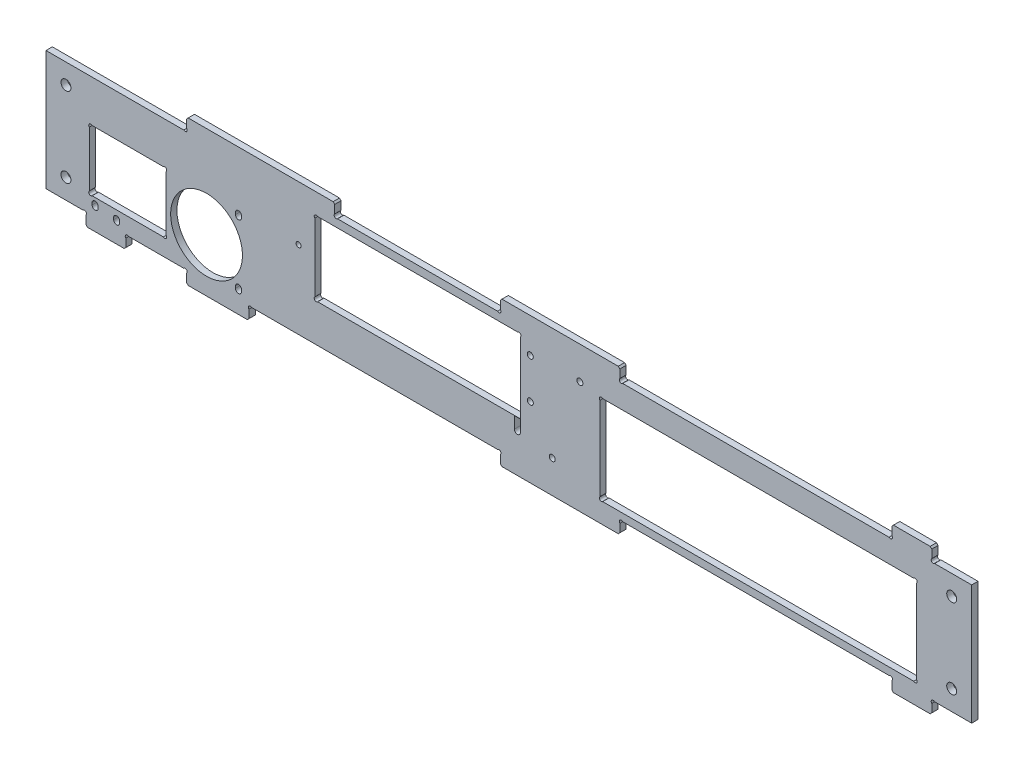
SolidWorks part; units mm, degrees
ref_plane "Front Plane" through (0, 0, 0) normal (0, 0, 1) x (1, 0, 0)
ref_plane "Top Plane" through (0, 0, 0) normal (0, 1, 0) x (1, 0, 0)
ref_plane "Right Plane" through (0, 0, 0) normal (1, 0, 0) x (0, 0, -1)
sketch "Sketch1" plane through (0, 0, 0) normal (0, 0, -1) x (-1, 0, 0)
  line L1 (-443.68, 0) -> (20.2, 0)
  line L2 (-443.68, 0) -> (-443.68, 60)
  line L3 (-443.68, 60) -> (20.2, 60)
  line L4 (20.2, 0) -> (20.2, 60)
extrude "Boss-Extrude1" add sketch "Sketch1" along normal up to vertex (3.175 mm away)
sketch "Sketch7" plane through (0, 0, -3.175) normal (0, 0, -1) x (-1, 0, 0)
  line L0 (-433.68, 50) -> (-433.68, 10) construction
  line L1 (10.2, 50) -> (10.2, 10) construction
  circle A0 centre (-433.68, 30) radius 2.5 construction
  circle A1 centre (10.2, 30) radius 2.5 construction
  circle A2 centre (-433.68, 50) radius 2.5
  circle A3 centre (-433.68, 10) radius 2.5
  circle A4 centre (10.2, 10) radius 2.5
  circle A5 centre (10.2, 50) radius 2.5
  point P10 (-433.68, 30)
  point P11 (10.2, 30)
  dimension "D2" = 5
  dimension "D1" = 20
extrude "Cut-Extrude5" cut sketch "Sketch7" against normal through all
sketch "Sketch2" plane through (0, 0, -3.175) normal (0, 0, -1) x (-1, 0, 0)
  line L0 (-216.5, 19) -> (-216.5, 58) construction
  line L1 (-217.5, 56) -> (-114.5, 56)
  line L2 (-217.5, 56) -> (-217.5, 19)
  line L3 (-217.5, 19) -> (-114.5, 19)
  line L4 (-114.5, 56) -> (-114.5, 19)
  line L5 (-107.5, 58) -> (-216.5, 58) construction
  line L6 (-216.5, 19) -> (-108.5, 19) construction
  line L7 (-108.5, 39) -> (-103.5, 44) construction
  line L8 (-103.5, 34) -> (-108.5, 39) construction
  line L9 (-222.5, 49) -> (-222.5, 29) construction
  line L10 (-217.5, 13) -> (-214.5, 13) construction
  line L11 (-217.5, 13) -> (-217.5, 18.9)
  line L12 (-217.5, 18.9) -> (-214.5, 18.9)
  line L13 (-214.5, 13) -> (-214.5, 18.9)
  line L14 (-216, 18.9) -> (-216, 13) construction
  line L15 (-217.5, 15.95) -> (-214.5, 15.95) construction
  circle A0 centre (-106.3787, 39) radius 1.5 construction
  circle A1 centre (-106.3787, 39) radius 1.25
  arc A2 (-217.5, 13) -> (-214.5, 13) centre (-216, 13) ccw
  circle A3 centre (-222.5, 49) radius 1.5
  circle A4 centre (-222.5, 29) radius 1.5
  point P18 (-216, 15.95)
  point P22 (-216, 11.5)
  point P27 (-222.5, 39)
  dimension "D4" = 3
  dimension "D5" = 2.5
  dimension "D9" = 3
  dimension "D1" = 1
  dimension "D2" = 6
  dimension "D3" = 2
  dimension "D6" = 0.1
  dimension "D7" = 3
  dimension "D8" = 6
  dimension "D10" = 5
  dimension "D11" = 20
extrude "Cut-Extrude1" cut sketch "Sketch2" against normal through all
sketch "Sketch3" plane through (0, 0, -3.175) normal (0, 0, -1) x (-1, 0, 0)
  line L1 (-257.37, 3.7) -> (-416.12, 3.7)
  line L2 (-257.37, 3.7) -> (-257.37, 48.4)
  line L3 (-257.37, 48.4) -> (-416.12, 48.4)
  line L4 (-416.12, 3.7) -> (-416.12, 48.4)
  line L5 (-336.745, 48.4) -> (-336.745, 3.7) construction
  line L6 (-257.37, 26.05) -> (-416.12, 26.05) construction
  point P0 (-336.745, 26.05)
extrude "Cut-Extrude2" cut sketch "Sketch3" against normal through all
sketch "Sketch4" plane through (0, 0, -3.175) normal (0, 0, -1) x (-1, 0, 0)
  line L1 (-76.25, 4.25) -> (-76.25, 5.25) construction
  line L2 (-77.75, 4.25) -> (-77.75, 5.25)
  line L3 (-74.75, 4.25) -> (-74.75, 5.25)
  line L4 (-76.25, 36.25) -> (-76.25, 37.25) construction
  line L5 (-77.75, 36.25) -> (-77.75, 37.25)
  line L6 (-74.75, 36.25) -> (-74.75, 37.25)
  line L7 (-15.2, 3.5) -> (-15.2, 4.5) construction
  line L8 (-16.7, 3.5) -> (-16.7, 4.5)
  line L9 (-13.7, 3.5) -> (-13.7, 4.5)
  line L10 (-4.4, 4.5) -> (-4.4, 5.5) construction
  line L11 (-5.9, 4.5) -> (-5.9, 5.5)
  line L12 (-2.9, 4.5) -> (-2.9, 5.5)
  line L13 (-40, 0) -> (-40, 40.5) construction
  line L14 (-1.5, 39) -> (-40, 39)
  line L15 (-1.5, 39) -> (-1.5, 8.5)
  line L16 (-1.5, 8.5) -> (-40, 8.5)
  line L17 (-40, 39) -> (-40, 8.5)
  line L18 (-81.5, 40.5) -> (0, 40.5) construction
  line L19 (0, 40.5) -> (0, 0) construction
  arc A0 (-77.75, 4.25) -> (-74.75, 4.25) centre (-76.25, 4.25) ccw
  arc A1 (-74.75, 5.25) -> (-77.75, 5.25) centre (-76.25, 5.25) ccw
  arc A2 (-77.75, 36.25) -> (-74.75, 36.25) centre (-76.25, 36.25) ccw
  arc A3 (-74.75, 37.25) -> (-77.75, 37.25) centre (-76.25, 37.25) ccw
  arc A4 (-16.7, 3.5) -> (-13.7, 3.5) centre (-15.2, 3.5) ccw
  arc A5 (-13.7, 4.5) -> (-16.7, 4.5) centre (-15.2, 4.5) ccw
  arc A6 (-5.9, 4.5) -> (-2.9, 4.5) centre (-4.4, 4.5) ccw
  arc A7 (-2.9, 5.5) -> (-5.9, 5.5) centre (-4.4, 5.5) ccw
  circle A8 centre (-60.25, 20.25) radius 18
  point P4 (-76.25, 4.75)
  point P9 (-76.25, 36.75)
  point P18 (-15.2, 4)
  point P27 (-4.4, 5)
  point P54 (-4.4, 7)
  dimension "D1" = 36
  dimension "D2" = 1.5
  dimension "D3" = 1.5
  dimension "D4" = 1.5
extrude "Cut-Extrude3" cut sketch "Sketch4" against normal through all
sketch "Sketch5" plane through (0, 0, -3.175) normal (0, 0, -1) x (-1, 0, 0)
  line L0 (-81.5, 0) -> (0, 0) construction
  line L1 (-81.5, -6.35) -> (-50.25, -6.35)
  line L2 (-81.5, -6.35) -> (-81.5, 0)
  line L3 (-81.5, 0) -> (-50.25, 0)
  line L4 (-50.25, -6.35) -> (-50.25, 0)
  line L5 (-65.875, 0) -> (-65.875, -6.35) construction
  line L6 (-81.5, -3.175) -> (-50.25, -3.175) construction
  line L8 (0, 0) -> (-81.5, 0) construction
  line L9 (-19.8, -6.35) -> (0.2, -6.35)
  line L10 (-19.8, -6.35) -> (-19.8, 0)
  line L11 (-19.8, 0) -> (0.2, 0)
  line L12 (0.2, -6.35) -> (0.2, 0)
  line L13 (-9.8, 0) -> (-9.8, -6.35) construction
  line L14 (-19.8, -3.175) -> (0.2, -3.175) construction
  line L15 (-15.2, 4) -> (-4.4, 5) construction
  line L16 (-443.68, 60) -> (20.2, 60) construction
  line L17 (-124.5, 66.35) -> (-50.25, 66.35)
  line L18 (-124.5, 66.35) -> (-124.5, 60)
  line L19 (-124.5, 60) -> (-50.25, 60)
  line L20 (-50.25, 66.35) -> (-50.25, 60)
  line L21 (-87.375, 60) -> (-87.375, 66.35) construction
  line L22 (-124.5, 63.175) -> (-50.25, 63.175) construction
  line L24 (-217.5, 56) -> (-217.5, 19) construction
  line L25 (-267.37, 66.35) -> (-207.5, 66.35)
  line L26 (-267.37, 66.35) -> (-267.37, 60)
  line L27 (-267.37, 60) -> (-207.5, 60)
  line L28 (-207.5, 66.35) -> (-207.5, 60)
  line L29 (-237.435, 60) -> (-237.435, 66.35) construction
  line L30 (-267.37, 63.175) -> (-207.5, 63.175) construction
  line L31 (-257.37, 3.7) -> (-257.37, 48.4) construction
  line L32 (-81.5, 40.5) -> (-81.5, 0) construction
  line L33 (-267.37, -6.35) -> (-207.5, -6.35)
  line L34 (-267.37, -6.35) -> (-267.37, 0)
  line L35 (-267.37, 0) -> (-207.5, 0)
  line L36 (-207.5, -6.35) -> (-207.5, 0)
  line L37 (-237.435, 0) -> (-237.435, -6.35) construction
  line L38 (-267.37, -3.175) -> (-207.5, -3.175) construction
  line L39 (-403.68, 66.35) -> (-423.68, 66.35)
  line L40 (-403.68, 66.35) -> (-403.68, 60)
  line L41 (-403.68, 60) -> (-423.68, 60)
  line L42 (-423.68, 66.35) -> (-423.68, 60)
  line L43 (-413.68, 60) -> (-413.68, 66.35) construction
  line L44 (-403.68, 63.175) -> (-423.68, 63.175) construction
  line L45 (-423.68, -6.35) -> (-403.68, -6.35)
  line L46 (-423.68, -6.35) -> (-423.68, 0)
  line L47 (-423.68, 0) -> (-403.68, 0)
  line L48 (-403.68, -6.35) -> (-403.68, 0)
  line L49 (-413.68, 0) -> (-413.68, -6.35) construction
  line L50 (-423.68, -3.175) -> (-403.68, -3.175) construction
  line L51 (-60.25, 36.25) -> (-60.25, 4.25) construction
  line L53 (200912.2132, 66.35) -> (-249087.7868, 66.35) construction
  line L54 (201107.5187, -6.35) -> (-248892.4813, -6.35) construction
  line L55 (-114.5, 56) -> (-114.5, 19) construction
  point P0 (-65.875, -3.175)
  point P10 (-9.8, -3.175)
  point P18 (-9.8, 4.5)
  point P20 (-87.375, 63.175)
  point P29 (-237.435, 63.175)
  point P34 (-237.435, -3.175)
  point P39 (-413.68, -3.175)
  point P41 (-413.68, 63.175)
  dimension "D1" = 10
  dimension "D2" = 20
  dimension "D3" = 10
  dimension "D4" = 10
  dimension "D5" = 20
  dimension "D6" = 10
  dimension "D7" = 10
extrude "Boss-Extrude2" add sketch "Sketch5" against normal up to surface (3.175 mm away) up to face at (20.75, 23.75, 0)
sketch "Sketch6" plane through (0, 0, -3.175) normal (0, 0, -1) x (-1, 0, 0)
  line L0 (-257.37, 3.7) -> (-257.37, 48.4) construction
  line L1 (200898.6873, 60) -> (-249101.3127, 60) construction
  line L2 (201114.3644, 0) -> (-248885.6356, 0) construction
  circle A0 centre (-247.37, 50) radius 1.5
  circle A1 centre (-233.5, 10) radius 1.5
  dimension "D1" = 3
  dimension "D2" = 10
  dimension "D3" = 10
  dimension "D4" = 10
  dimension "D5" = 10
extrude "Cut-Extrude4" cut sketch "Sketch6" against normal through all
sketch "Sketch8" plane through (0, 0, -3.175) normal (0, 0, -1) x (-1, 0, 0)
  line L0 (-415.4129, 48.6929) -> (-415.4129, 48.4) construction
  line L1 (-257.37, 48.4) -> (-416.12, 48.4) construction
  line L2 (-416.4129, 47.6929) -> (-416.12, 47.6929) construction
  line L3 (-416.12, 3.7) -> (-416.12, 48.4) construction
  line L4 (-415.4129, 4.4071) -> (-416.12, 4.4071) construction
  line L5 (-415.4129, 47.6929) -> (-416.12, 47.6929) construction
  line L6 (-258.0771, 47.6929) -> (-257.37, 47.6929) construction
  line L7 (-257.37, 3.7) -> (-257.37, 48.4) construction
  line L8 (-258.0771, 4.4071) -> (-257.37, 4.4071) construction
  line L9 (-216.7929, 55.2929) -> (-217.5, 55.2929) construction
  line L10 (-217.5, 56) -> (-217.5, 19) construction
  line L11 (-115.2071, 55.2929) -> (-114.5, 55.2929) construction
  line L12 (-114.5, 56) -> (-114.5, 19) construction
  line L13 (-115.2071, 19.7071) -> (-114.5, 19.7071) construction
  line L14 (-402.9729, -0.7071) -> (-402.9729, 0) construction
  line L15 (-403.68, 0) -> (-267.37, 0) construction
  line L16 (-424.3871, -0.7071) -> (-424.3871, 0) construction
  line L17 (-443.68, 0) -> (-423.68, 0) construction
  line L18 (-268.0771, -0.7071) -> (-268.0771, 0) construction
  line L19 (-206.7929, -0.7071) -> (-206.7929, 0) construction
  line L20 (-207.5, 0) -> (-81.5, 0) construction
  line L21 (-82.2071, -0.7071) -> (-82.2071, 0) construction
  line L22 (-49.5429, -0.7071) -> (-49.5429, 0) construction
  line L23 (-50.25, 0) -> (-19.8, 0) construction
  line L24 (-20.5071, -0.7071) -> (-20.5071, 0) construction
  line L25 (0.9071, -0.7071) -> (0.9071, 0) construction
  line L26 (0.2, 0) -> (20.2, 0) construction
  line L27 (-424.3871, 60.7071) -> (-424.3871, 60) construction
  line L28 (-423.68, 60) -> (-443.68, 60) construction
  line L29 (-402.9729, 60.7071) -> (-402.9729, 60) construction
  line L30 (-267.37, 60) -> (-403.68, 60) construction
  line L31 (-268.0771, 60.7071) -> (-268.0771, 60) construction
  line L32 (-206.7929, 60.7071) -> (-206.7929, 60) construction
  line L33 (-124.5, 60) -> (-207.5, 60) construction
  line L34 (-125.2071, 60.7071) -> (-125.2071, 60) construction
  line L35 (-49.5429, 60.7071) -> (-49.5429, 60) construction
  line L36 (20.2, 60) -> (-50.25, 60) construction
  line L37 (-39.2929, 38.2929) -> (-39.2929, 39) construction
  line L38 (-2.2071, 38.2929) -> (-2.2071, 39) construction
  line L39 (-2.2071, 9.2071) -> (-2.2071, 8.5) construction
  line L40 (-39.2929, 9.2071) -> (-39.2929, 8.5) construction
  line L41 (-1.5, 8.5) -> (-40, 8.5) construction
  line L42 (-1.5, 39) -> (-40, 39) construction
  circle A0 centre (-415.4129, 47.6929) radius 1
  circle A1 centre (-258.0771, 47.6929) radius 1
  circle A2 centre (-258.0771, 4.4071) radius 1
  circle A3 centre (-415.4129, 4.4071) radius 1
  circle A4 centre (-216.7929, 55.2929) radius 1
  circle A5 centre (-115.2071, 55.2929) radius 1
  circle A6 centre (-115.2071, 19.7071) radius 1
  circle A7 centre (-424.3871, 60.7071) radius 1
  circle A8 centre (-402.9729, 60.7071) radius 1
  circle A9 centre (-268.0771, 60.7071) radius 1
  circle A10 centre (-206.7929, 60.7071) radius 1
  circle A11 centre (-125.2071, 60.7071) radius 1
  circle A12 centre (-49.5429, 60.7071) radius 1
  circle A13 centre (0.9071, -0.7071) radius 1
  circle A14 centre (-20.5071, -0.7071) radius 1
  circle A15 centre (-49.5429, -0.7071) radius 1
  circle A16 centre (-82.2071, -0.7071) radius 1
  circle A17 centre (-206.7929, -0.7071) radius 1
  circle A18 centre (-268.0771, -0.7071) radius 1
  circle A19 centre (-402.9729, -0.7071) radius 1
  circle A20 centre (-424.3871, -0.7071) radius 1
  circle A21 centre (-39.2929, 38.2929) radius 1
  circle A22 centre (-2.2071, 38.2929) radius 1
  circle A23 centre (-39.2929, 9.2071) radius 1
  circle A24 centre (-2.2071, 9.2071) radius 1
  point P3 (-415.4129, 48.6929)
  point P4 (-416.4129, 47.6929)
  dimension "D1" = 2
extrude "Cut-Extrude7" cut sketch "Sketch8" against normal through all
chamfer "Chamfer2" distance 0.8 angle 45 14 edges at (50.25, 66.35, -1.5875) (124.5, 66.35, -1.5875) (207.5, 66.35, -1.5875) (267.37, 66.35, -1.5875) (403.68, 66.35, -1.5875) (423.68, 66.35, -1.5875) (423.68, -6.35, -1.5875) (403.68, -6.35, -1.5875) (267.37, -6.35, -1.5875) (207.5, -6.35, -1.5875) (81.5, -6.35, -1.5875) (50.25, -6.35, -1.5875) (19.8, -6.35, -1.5875) (-0.2, -6.35, -1.5875)
